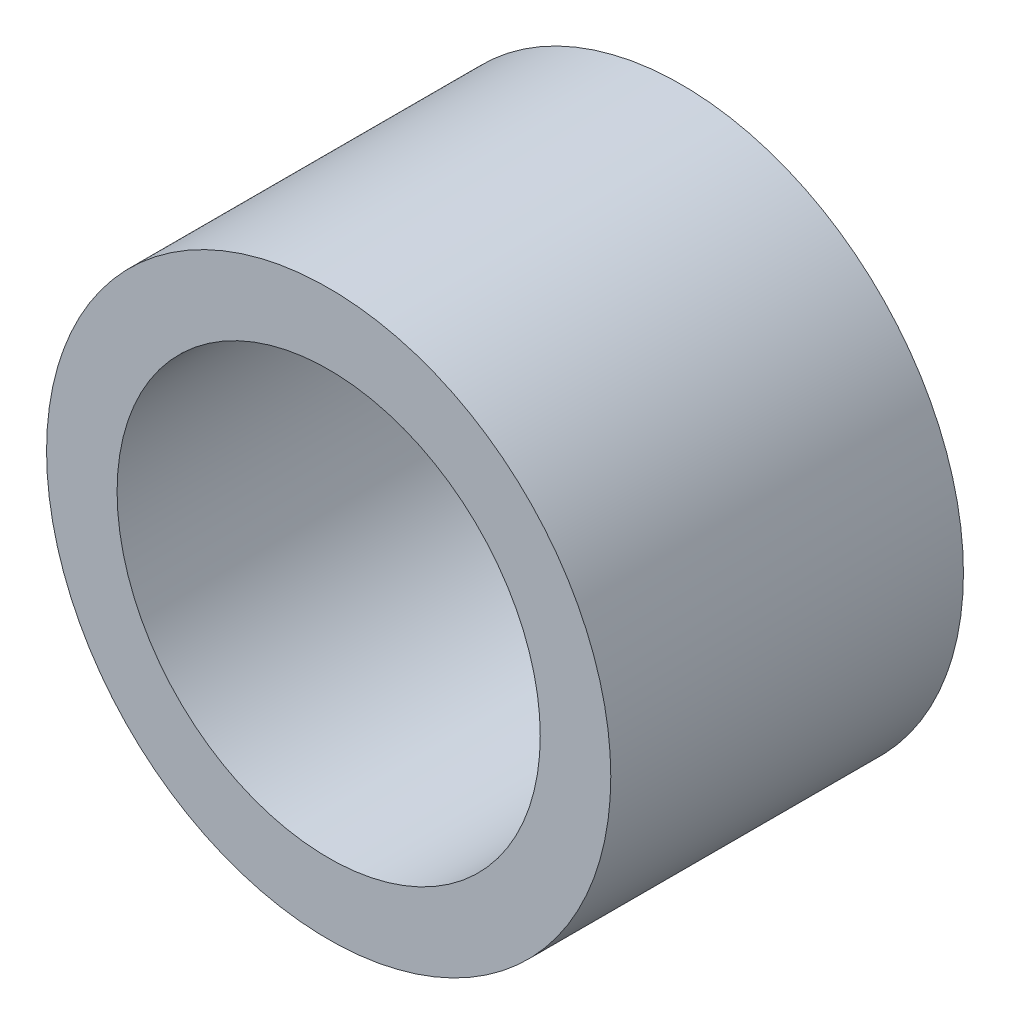
SolidWorks part; units mm, degrees
ref_plane "Plan de face" through (0, 0, 0) normal (0, 0, 1) x (1, 0, 0)
ref_plane "Plan de dessus" through (0, 0, 0) normal (0, 1, 0) x (1, 0, 0)
ref_plane "Plan de droite" through (0, 0, 0) normal (1, 0, 0) x (0, 0, -1)
sketch "Esquisse2" plane through (0, 0, 0) normal (0, 0, 1) x (1, 0, 0)
  circle A0 centre (0, 0) radius 4.5
  circle A1 centre (0, 0) radius 6
  dimension "D1" = 9
  dimension "D2" = 0
extrude "Boss.-Extru.1" add sketch "Esquisse2" along normal blind 7.5
